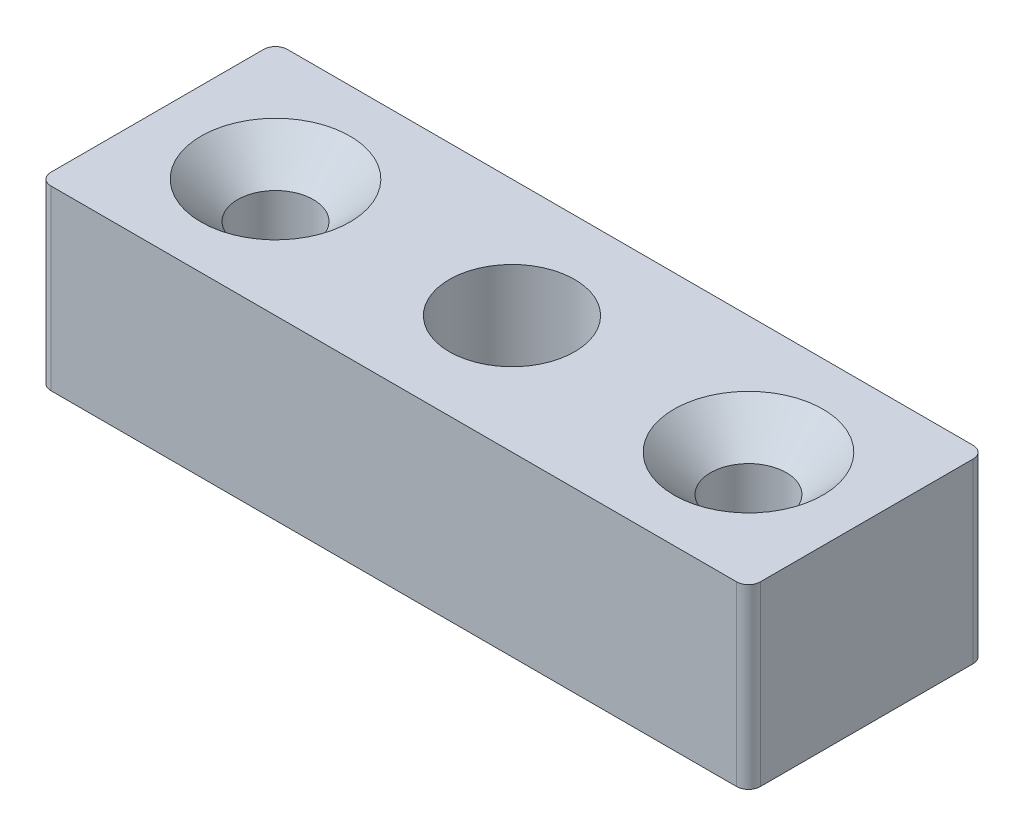
SolidWorks part; units mm, degrees
material "ABS"
ref_plane "Front Plane" through (0, 0, 0) normal (0, 0, 1) x (1, 0, 0)
ref_plane "Top Plane" through (0, 0, 0) normal (0, 1, 0) x (1, 0, 0)
ref_plane "Right Plane" through (0, 0, 0) normal (1, 0, 0) x (0, 0, -1)
sketch "Sketch1" plane through (0, 0, 0) normal (0, 1, 0) x (1, 0, 0)
  line L0 (-10, 0) -> (10, 0) construction
  line L1 (-15, 5) -> (15, 5)
  line L2 (-15, 5) -> (-15, -5)
  line L3 (-15, -5) -> (15, -5)
  line L4 (15, 5) -> (15, -5)
  circle A0 centre (-10, 0) radius 1.5 construction
  circle A1 centre (10, 0) radius 1.5 construction
  circle A2 centre (0, 0) radius 2.5 construction
  point P4 (0, -5)
  point P6 (-15, 0)
  point P11 (0, 0)
  dimension "D3" = 3
  dimension "D5" = 5
  dimension "D1" = 30
  dimension "D2" = 10
  dimension "D4" = 20
extrude "Boss-Extrude1" add sketch "Sketch1" against normal blind 7.5
hole_wizard "CSK for M3 Flat Head Machine Screw1" positions "3DSketch1" profile "Sketch2" countersink size "M3" standard "ANSI Metric" end condition up to next
sketch3d "3DSketch1"
  point P0 (-10, 0, 0)
  point P2 (10, 0, 0)
sketch "Sketch2" plane through (-10, 0, 0) normal (1, 0, 0) x (0, 0, 1)
  line L0 (0, 0) -> (0, 7.5)
  line L1 (0, 7.5) -> (1.6, 7.5)
  line L2 (1.6, 7.5) -> (1.6, 1.55)
  line L3 (1.6, 1.55) -> (3.15, 0)
  line L5 (3.15, 0) -> (0, 0)
  line L6 (-1.6, 1.55) -> (-3.15, 0) construction
  line L11 (0, -6.35) -> (0, 107.95) construction
  dimension "Thru Hole Dia." = 3.2
  dimension "Thru Hole Depth" = 7.5
  dimension "Near C'Sink Dia." = 6.3
  dimension "Near C'Sink Angle" = 90
hole_wizard "M5 Clearance Hole1" positions "3DSketch2" profile "Sketch3" hole size "M5" standard "ANSI Metric" end condition up to next
sketch3d "3DSketch2"
  point P0 (0, 0, 0)
  point P4 (0, 0, 0)
sketch "Sketch3" plane through (0, 0, 0) normal (1, 0, 0) x (0, 0, 1)
  line L0 (0, 0) -> (0, 7.5)
  line L1 (0, 7.5) -> (2.65, 7.5)
  line L2 (2.65, 7.5) -> (2.65, 0)
  line L5 (2.65, 0) -> (0, 0)
  line L11 (0, -6.35) -> (0, 107.95) construction
  dimension "Thru Hole Dia." = 5.3
  dimension "Thru Hole Depth" = 7.5
fillet "Fillet1" radius 0.5 4 edges at (-15, -3.75, -5) (15, -3.75, -5) (15, -3.75, 5) (-15, -3.75, 5)
